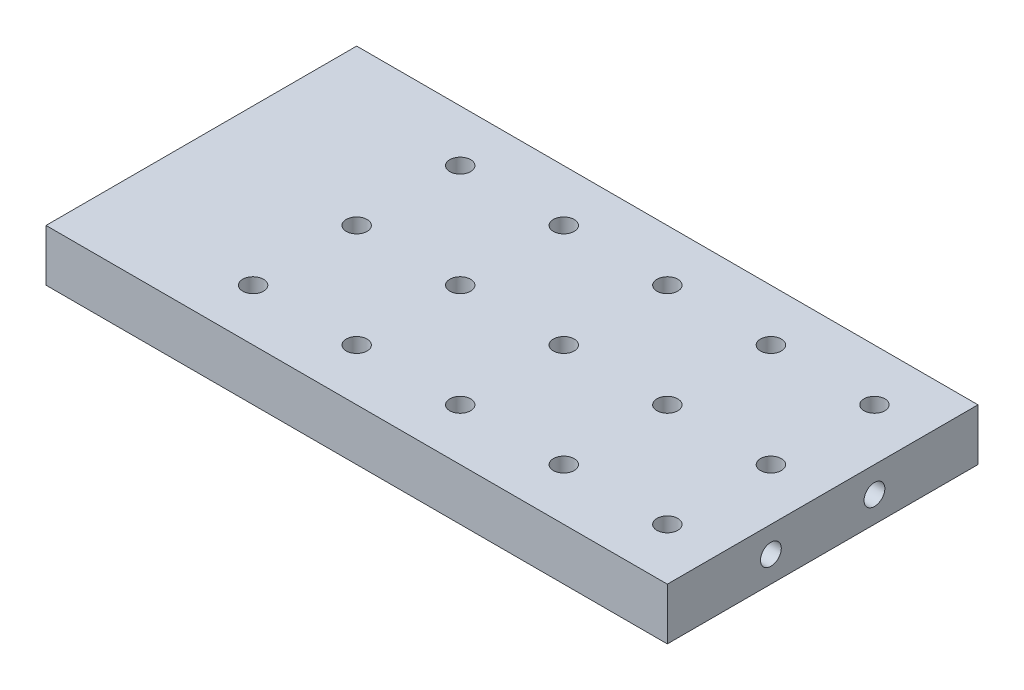
SolidWorks part; units mm, degrees
ref_plane "Front Plane" through (0, 0, 0) normal (0, 0, 1) x (1, 0, 0)
ref_plane "Top Plane" through (0, 0, 0) normal (0, 1, 0) x (1, 0, 0)
ref_plane "Right Plane" through (0, 0, 0) normal (1, 0, 0) x (0, 0, -1)
sketch "Sketch1" plane through (0, 0, 0) normal (0, 1, 0) x (1, 0, 0)
  line L1 (-76.2, -38.1) -> (76.2, -38.1)
  line L2 (-76.2, -38.1) -> (-76.2, 38.1)
  line L3 (-76.2, 38.1) -> (76.2, 38.1)
  line L4 (76.2, -38.1) -> (76.2, 38.1)
  line L5 (-76.2, -38.1) -> (76.2, 38.1) construction
  line L6 (-76.2, 38.1) -> (76.2, -38.1) construction
  point P0 (0, 0)
  dimension "D1" = 152.4
  dimension "D2" = 76.2
extrude "Boss-Extrude1" add sketch "Sketch1" along normal mid plane 12.7
hole_wizard "Tap Drill for 1/4-20 Tap1" positions "Sketch2" profile "Sketch3" hole size "1/4-20" standard "ANSI Inch"
sketch "Sketch2" plane through (0, 6.35, 0) normal (0, 1, 0) x (1, 0, 0)
  line L1 (76.2, -38.1) -> (76.2, 38.1) construction
  point P0 (63.5, 25.4)
  point P10 (38.1, 25.4)
  point P11 (12.7, 25.4)
  point P13 (38.1, 0)
  point P14 (12.7, 0)
  point P16 (38.1, -25.4)
  point P17 (12.7, -25.4)
  point P19 (63.5, 0)
  point P20 (63.5, -25.4)
  point P26 (-12.7, 25.4)
  point P27 (-38.1, 25.4)
  point P28 (-12.7, 0)
  point P29 (-38.1, 0)
  point P30 (-12.7, -25.4)
  point P31 (-38.1, -25.4)
  dimension "D1" = 25.4
  dimension "D2" = 12.7
  dimension "D3" = 5
  dimension "D4" = 3
sketch "Sketch3" plane through (63.5, 6.35, -25.4) normal (1, 0, 0) x (0, 0, 1)
  line L0 (0, 0) -> (0, 12.7)
  line L1 (0, 12.7) -> (2.5527, 12.7)
  line L2 (2.5527, 12.7) -> (2.5527, 0)
  line L5 (2.5527, 0) -> (0, 0)
  line L11 (0, -6.35) -> (0, 107.95) construction
  dimension "Thru Hole Dia." = 5.1054
  dimension "Thru Hole Depth" = 12.7
hole_wizard "Tap Drill for 1/4-20 Tap2" positions "Sketch4" profile "Sketch5" hole size "1/4-20" standard "ANSI Inch"
sketch "Sketch4" plane through (-76.2, 0, 0) normal (-1, 0, 0) x (0, 0, 1)
  line L0 (-38.1, 6.35) -> (-38.1, -6.35) construction
  point P0 (-25.4, 0)
  point P10 (-38.1, 0)
  point P14 (0, 0)
  point P15 (25.4, 0)
  dimension "D1" = 25.4
  dimension "D2" = 3
sketch "Sketch5" plane through (-76.2, 0, -25.4) normal (0, 1, 0) x (0, 0, 1)
  line L0 (0, 0) -> (0, 14.2338)
  line L1 (0, 14.2338) -> (2.5527, 12.7)
  line L2 (2.5527, 12.7) -> (2.5527, 0)
  line L5 (2.5527, 0) -> (0, 0)
  line L10 (0, 14.2338) -> (-2.5527, 12.7) construction
  line L11 (0, -6.35) -> (0, 107.95) construction
  dimension "Hole Dia." = 5.1054
  dimension "Hole Depth" = 12.7
  dimension "Drill Angle" = 118
hole_wizard "Tap Drill for 1/4-20 Tap3" positions "Sketch6" profile "Sketch7" hole size "1/4-20" standard "ANSI Inch"
sketch "Sketch6" plane through (76.2, 0, 0) normal (1, 0, 0) x (0, 0, -1)
  point P0 (12.7, 0)
  point P2 (-12.7, 0)
  dimension "D1" = 12.7
  dimension "D2" = 12.7
sketch "Sketch7" plane through (76.2, 0, -12.7) normal (0, 1, 0) x (0, 0, -1)
  line L0 (0, 0) -> (0, 14.2338)
  line L1 (0, 14.2338) -> (2.5527, 12.7)
  line L2 (2.5527, 12.7) -> (2.5527, 0)
  line L5 (2.5527, 0) -> (0, 0)
  line L10 (0, 14.2338) -> (-2.5527, 12.7) construction
  line L11 (0, -6.35) -> (0, 107.95) construction
  dimension "Hole Dia." = 5.1054
  dimension "Hole Depth" = 12.7
  dimension "Drill Angle" = 118
